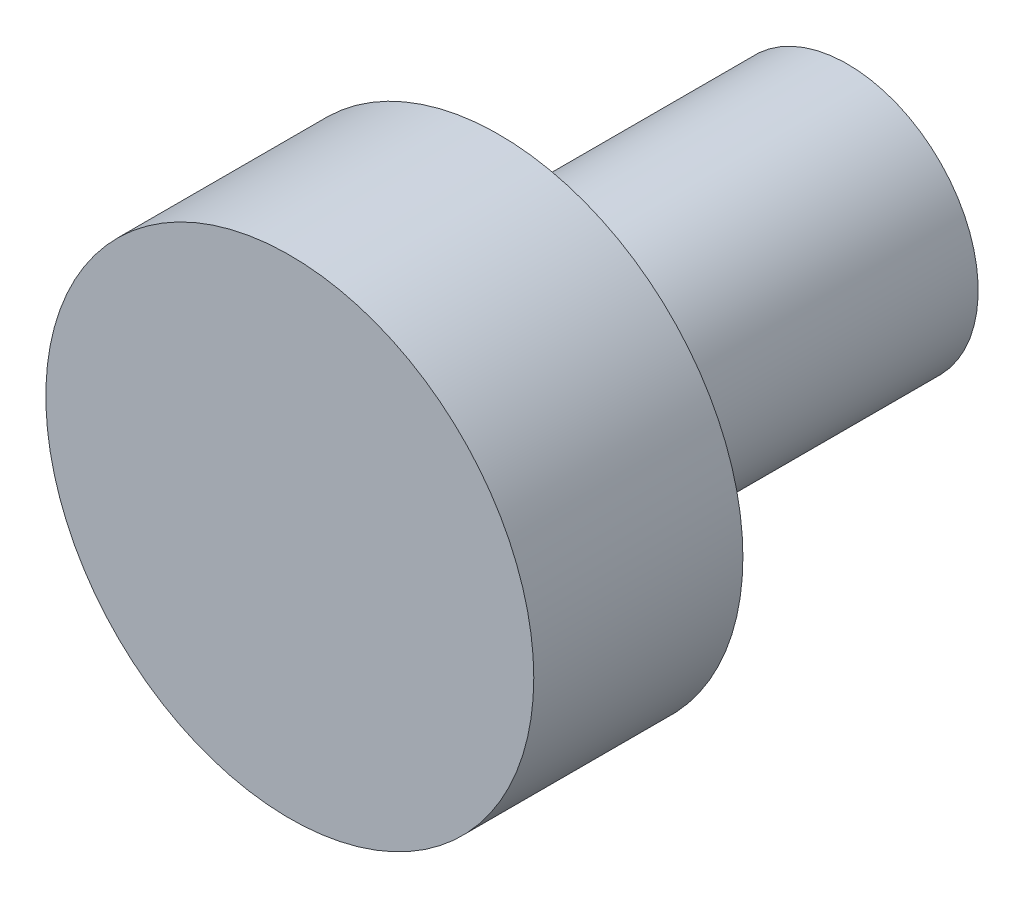
SolidWorks part; units mm, degrees
ref_plane "Plan de face" through (0, 0, 0) normal (0, 0, 1) x (1, 0, 0)
ref_plane "Plan de dessus" through (0, 0, 0) normal (0, 1, 0) x (1, 0, 0)
ref_plane "Plan de droite" through (0, 0, 0) normal (1, 0, 0) x (0, 0, -1)
sketch "Esquisse1" plane through (0, 0, 0) normal (0, 0, 1) x (1, 0, 0)
  circle A0 centre (0, 0) radius 2.8
  dimension "D1" = 5.6
extrude "Boss.-Extru.1" add sketch "Esquisse1" along normal blind 2.4
sketch "Esquisse2" plane through (0, 0, 0) normal (0, 0, -1) x (-1, 0, 0)
  circle A0 centre (0, 0) radius 1.5
  dimension "D1" = 3
extrude "Boss.-Extru.2" add sketch "Esquisse2" along normal blind 4
